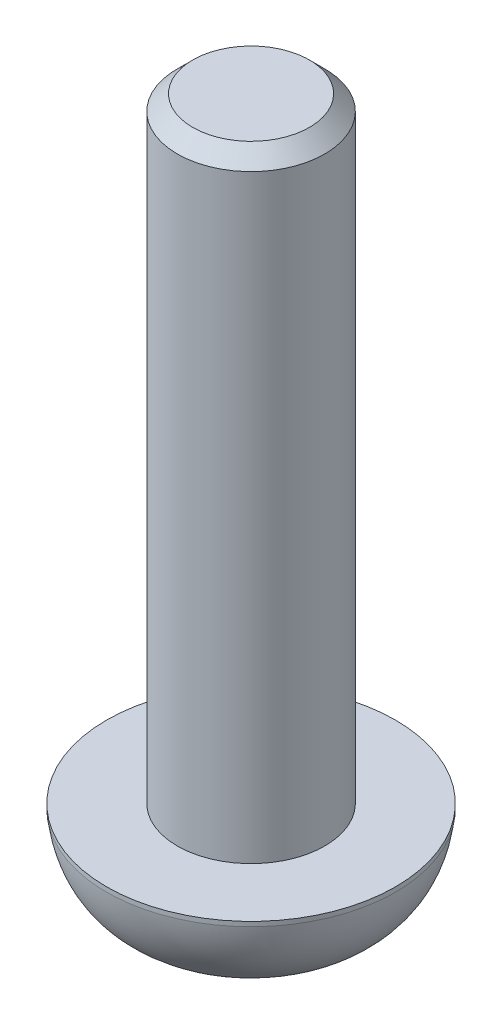
SolidWorks part; units mm, degrees
ref_plane "Front Plane" through (0, 0, 0) normal (0, 0, 1) x (1, 0, 0)
ref_plane "Top Plane" through (0, 0, 0) normal (0, 1, 0) x (1, 0, 0)
ref_plane "Right Plane" through (0, 0, 0) normal (1, 0, 0) x (0, 0, -1)
sketch "Sketch1" plane through (0, 0, 0) normal (0, 1, 0) x (1, 0, 0)
  circle A0 centre (0, 0) radius 4.7
  dimension "D1" = 9.4
extrude "Boss-Extrude1" add sketch "Sketch1" along normal blind 3
sketch "Sketch2" plane through (0, 3, 0) normal (0, 1, 0) x (1, 0, 0)
  circle A0 centre (0, 0) radius 2.4
  dimension "D1" = 4.8
extrude "Boss-Extrude2" add sketch "Sketch2" along normal blind 20
sketch "Sketch3" plane through (0, 0, 0) normal (0, 0, 1) x (1, 0, 0)
  line L0 (0, 0) -> (0, 3) construction
  line L1 (4.7, 3) -> (-4.7, 3) construction
  line L3 (-4.7, 0) -> (4.7, 0) construction
  line L4 (4.7, 0) -> (4.7, 3) construction
  line L5 (2.35, 0) -> (4.7, 0)
  line L6 (4.7, 0) -> (4.7, 2.85)
  spline S0 degree 2 poles (2.35, 0) (4.4325, 0.5996) (4.7, 2.85) knots 0 0 0 1 1 1
  dimension "D1" = 4.7
  dimension "D2" = 0.15
revolve "Cut-Revolve1" cut sketch "Sketch3" angle 360 about L0
sketch "Sketch4" plane through (0, 0, 0) normal (0, -1, 0) x (1, 0, 0)
  line L1 (0, 1.7321) -> (-1.5, 0.866)
  line L2 (-1.5, 0.866) -> (-1.5, -0.866)
  line L3 (-1.5, -0.866) -> (0, -1.7321)
  line L4 (0, -1.7321) -> (1.5, -0.866)
  line L5 (1.5, -0.866) -> (1.5, 0.866)
  line L6 (1.5, 0.866) -> (0, 1.7321)
  circle A0 centre (0, 0) radius 1.5 construction
  dimension "D1" = 3
extrude "Cut-Extrude1" cut sketch "Sketch4" against normal blind 1.5
chamfer "Chamfer1" distance 0.5 angle 45 1 edges at (0, 23, 2.4)
